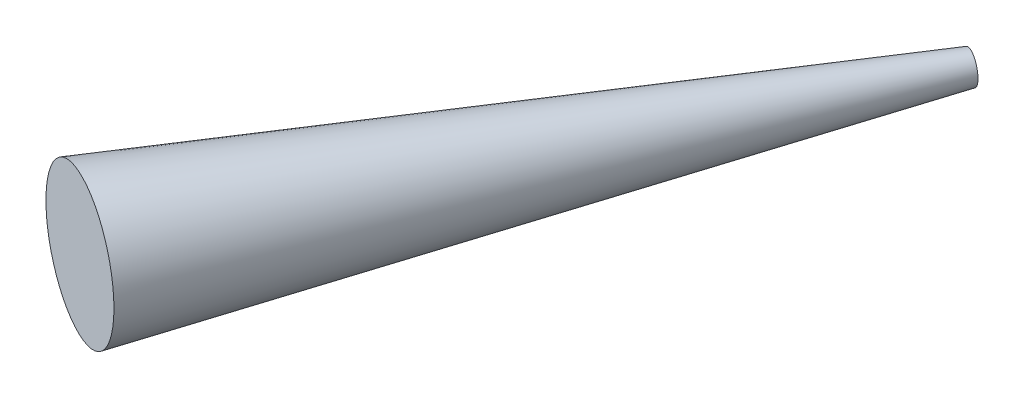
SolidWorks part; units mm, degrees
ref_plane "Front Plane" through (0, 0, 0) normal (0, 0, 1) x (1, 0, 0)
ref_plane "Top Plane" through (0, 0, 0) normal (0, 1, 0) x (1, 0, 0)
ref_plane "Right Plane" through (0, 0, 0) normal (1, 0, 0) x (0, 0, -1)
sketch "Sketch1" plane through (0, 0, 0) normal (0, 1, 0) x (1, 0, 0)
  line L1 (2.0652, -39.5672) -> (2.0652, -214.6868) construction
  line L3 (-29.2481, -40.0486) -> (-118.5511, -231.5596) construction
  line L13 (-29.2481, -40.0486) -> (-118.5511, -231.5596)
  line L19 (-29.2481, -40.0486) -> (-99.8887, -245.2039) construction
  line L20 (-118.5511, -231.5596) -> (-98.4225, -240.9458)
  line L21 (-98.4225, -240.9458) -> (-24.7369, -41.602)
  line L22 (-24.7369, -41.602) -> (-29.2481, -40.0486)
  dimension "D1" = 25
  dimension "D2" = 6
revolve "Revolve1" add sketch "Sketch1" angle 360 about L13
